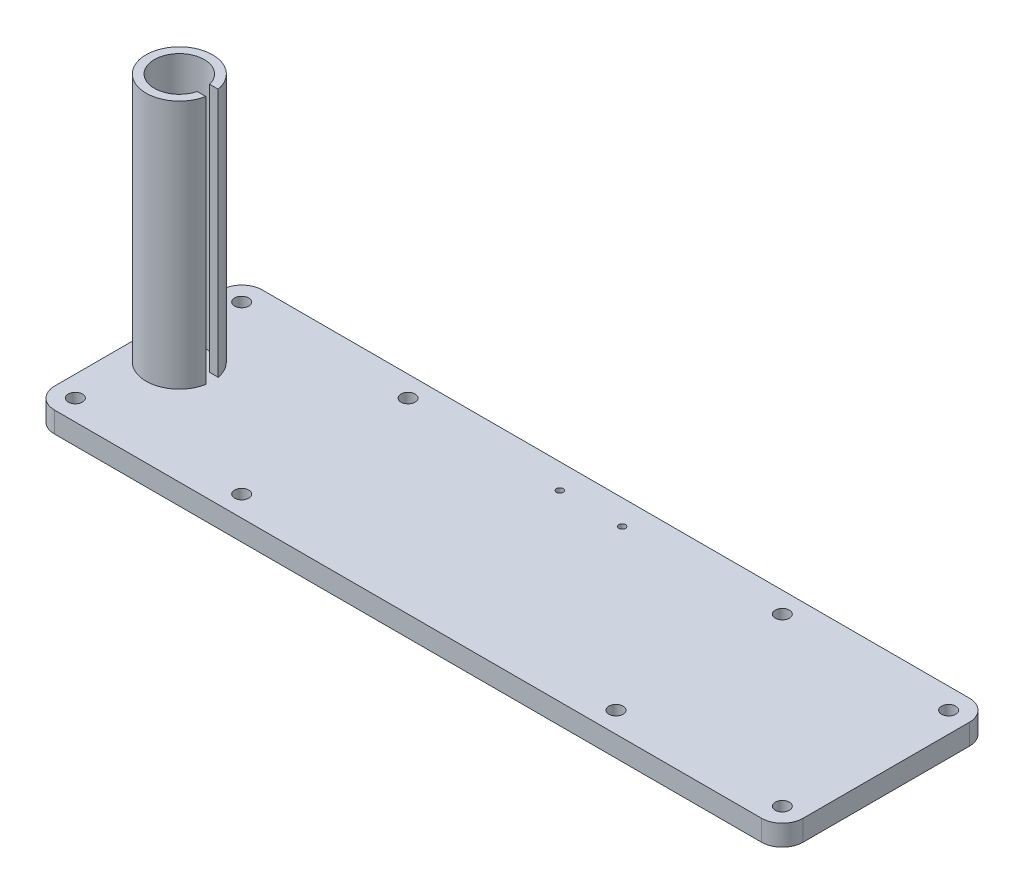
SolidWorks part; units mm, degrees
ref_plane "前视基准面" through (0, 0, 0) normal (0, 0, 1) x (1, 0, 0)
ref_plane "上视基准面" through (0, 0, 0) normal (0, 1, 0) x (1, 0, 0)
ref_plane "右视基准面" through (0, 0, 0) normal (1, 0, 0) x (0, 0, -1)
sketch "草图1" plane through (0, 0, 0) normal (0, 1, 0) x (1, 0, 0)
  line L1 (-85, 25) -> (85, 25)
  line L2 (-90, 20) -> (-90, -20)
  line L3 (-85, -25) -> (85, -25)
  line L4 (90, 20) -> (90, -20)
  line L5 (0, -25) -> (0, 25) construction
  line L6 (-90, 0) -> (90, 0) construction
  line L7 (-50, 25) -> (50, 25)
  line L8 (-50, 25) -> (-50, -25)
  line L9 (-50, -25) -> (50, -25)
  line L10 (50, 25) -> (50, -25)
  line L11 (0, -25) -> (0, 25) construction
  line L12 (-50, 0) -> (50, 0) construction
  circle A1 centre (-85, 20) radius 1.7
  circle A2 centre (-85, -20) radius 1.7
  circle A3 centre (85, 20) radius 1.7
  circle A4 centre (85, -20) radius 1.7
  arc A5 (-90, -20) -> (-85, -25) centre (-85, -20) ccw
  arc A6 (85, -25) -> (90, -20) centre (85, -20) ccw
  arc A7 (85, 25) -> (90, 20) centre (85, 20) cw
  arc A8 (-85, 25) -> (-90, 20) centre (-85, 20) ccw
  circle A15 centre (-45, 20) radius 1.7
  circle A16 centre (45, 20) radius 1.7
  circle A17 centre (45, -20) radius 1.7
  circle A18 centre (-45, -20) radius 1.7
  point P0 (0, 0)
  point P17 (0, 0)
  point P18 (-90, -25)
  point P23 (90, 25)
  point P26 (-90, 25)
  dimension "D3" = 3.4
  dimension "D4" = 5
  dimension "D5" = 3.4
  dimension "D6" = 5
  dimension "D1" = 50
  dimension "D2" = 180
  dimension "D7" = 5
  dimension "D8" = 5
  dimension "D9" = 5
  dimension "D12" = 100
extrude "凸台-拉伸1" add sketch "草图1" along normal blind 5 contours L10 L1 L8 L3 A16 A15 A17 A18 | L1 A8 L2 A5 L3 L8 A2 A1 | A7 L1 L10 L3 A6 L4 A4 A3
sketch "草图2" plane through (0, 5, 0) normal (0, 1, 0) x (1, 0, 0)
  line L0 (0, -1000) -> (0, 49000) construction
  line L1 (-85, 25) -> (85, 25) construction
  line L2 (-7.5, 25) -> (7.5, 25)
  line L3 (-7.5, 25) -> (-7.5, 19)
  line L4 (-7.5, 19) -> (7.5, 19)
  line L5 (7.5, 25) -> (7.5, 19)
  line L6 (0, 19) -> (0, 25) construction
  line L7 (-7.5, 22) -> (7.5, 22) construction
  line L9 (-10, 28.5) -> (10, 28.5) construction
  line L10 (-10, 28.5) -> (-10, 15.5) construction
  line L11 (-10, 15.5) -> (10, 15.5) construction
  line L12 (10, 28.5) -> (10, 15.5) construction
  line L13 (0, 15.5) -> (0, 28.5) construction
  line L14 (-10, 22) -> (10, 22) construction
  point P1 (0, 22)
  point P4 (7.5, 19)
  point P6 (-7.5, 19)
  point P9 (0, 22)
  dimension "D1" = 6
  dimension "D2" = 15
  dimension "D3" = 20
  dimension "D4" = 13
  dimension "D5" = 3.5
hole_wizard "M2 螺纹孔2" positions "草图2" profile "草图4" tap size "M2" standard "GB"
sketch "草图4" plane through (-7.5, 5, -19) normal (1, 0, 0) x (0, 0, 1)
  line L0 (0, 0) -> (0, 5)
  line L1 (0, 5) -> (0.8, 5)
  line L2 (0.8, 5) -> (0.8, 0)
  line L5 (0.8, 0) -> (0, 0)
  line L11 (0, -6.35) -> (0, 107.95) construction
  dimension "通孔螺纹孔钻头直径" = 1.6
  dimension "通孔螺纹孔钻头深度" = 5
cosmetic thread "孔螺纹线7" parameters "D2"=2
cosmetic thread "孔螺纹线8" parameters "D2"=2
sketch "草图8" plane through (0, 5, 0) normal (0, 1, 0) x (1, 0, 0)
  line L0 (-1000, 0) -> (49000, 0) construction
  line L1 (-90, 20) -> (-90, -20) construction
  circle A0 centre (-80, 0) radius 6
  dimension "D1" = 12
  dimension "D2" = 10
extrude "拉伸-薄壁1" add sketch "草图8" along normal blind 60 thin
sketch "草图9" plane through (0, 65, 0) normal (0, 1, 0) x (1, 0, 0)
  line L0 (-1000, 0) -> (49000, 0) construction
  line L1 (-74.1905, 1.5) -> (-72.1419, 1.5)
  line L2 (-74.1905, -1.5) -> (-72.1419, -1.5)
  circle A0 centre (-80, 0) radius 6 construction
  circle A1 centre (-80, 0) radius 8 construction
  circle A2 centre (-80, 0) radius 8 construction
  arc A3 (-72.1419, -1.5) -> (-72.1419, 1.5) centre (-80, 0) ccw
  arc A4 (-74.1905, -1.5) -> (-74.1905, 1.5) centre (-80, 0) ccw
  dimension "D1" = 3
extrude "切除-拉伸1" cut sketch "草图9" against normal up to surface (60 mm away) up to face at (-72, 5, 0)
